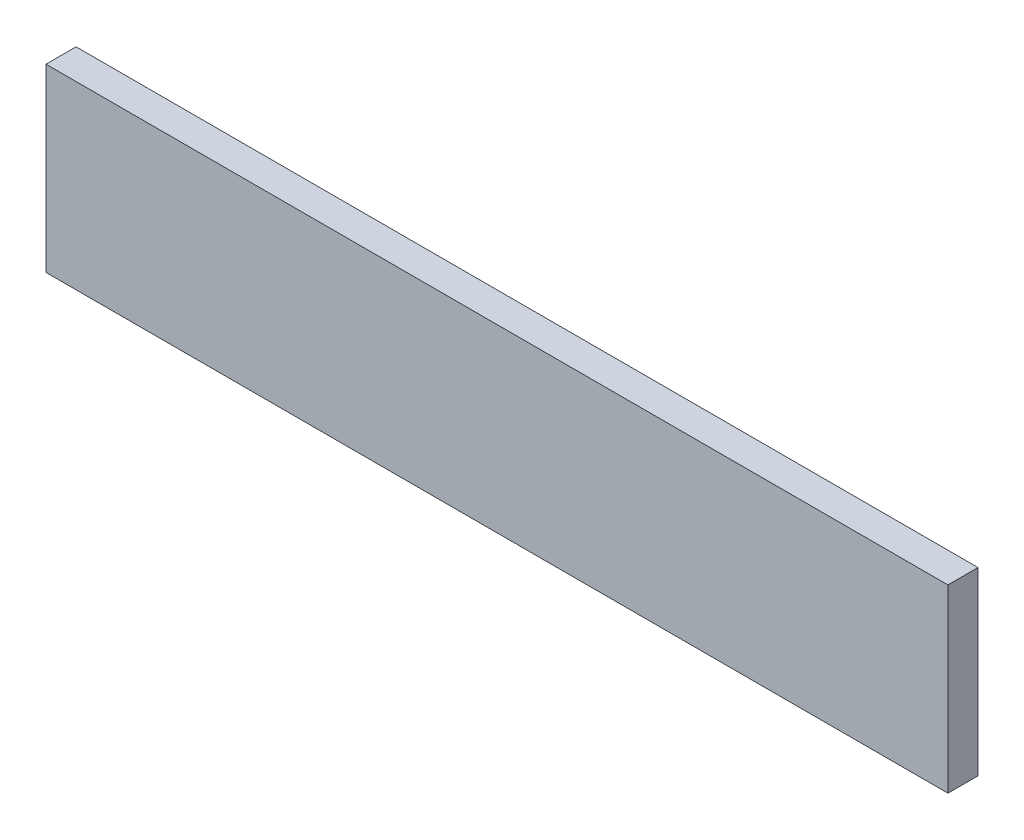
SolidWorks part; units mm, degrees
ref_plane "Спереди" through (0, 0, 0) normal (0, 0, 1) x (1, 0, 0)
ref_plane "Сверху" through (0, 0, 0) normal (0, 1, 0) x (1, 0, 0)
ref_plane "Справа" through (0, 0, 0) normal (1, 0, 0) x (0, 0, -1)
sketch "Эскиз1" plane through (0, 0, 0) normal (0, 0, 1) x (1, 0, 0)
  line L1 (0, 0) -> (300, 0)
  line L2 (0, 0) -> (0, 60)
  line L3 (0, 60) -> (300, 60)
  line L4 (300, 0) -> (300, 60)
  dimension "D1" = 300
  dimension "D2" = 60
extrude "Задняя панель каретки" add sketch "Эскиз1" along normal blind 10
